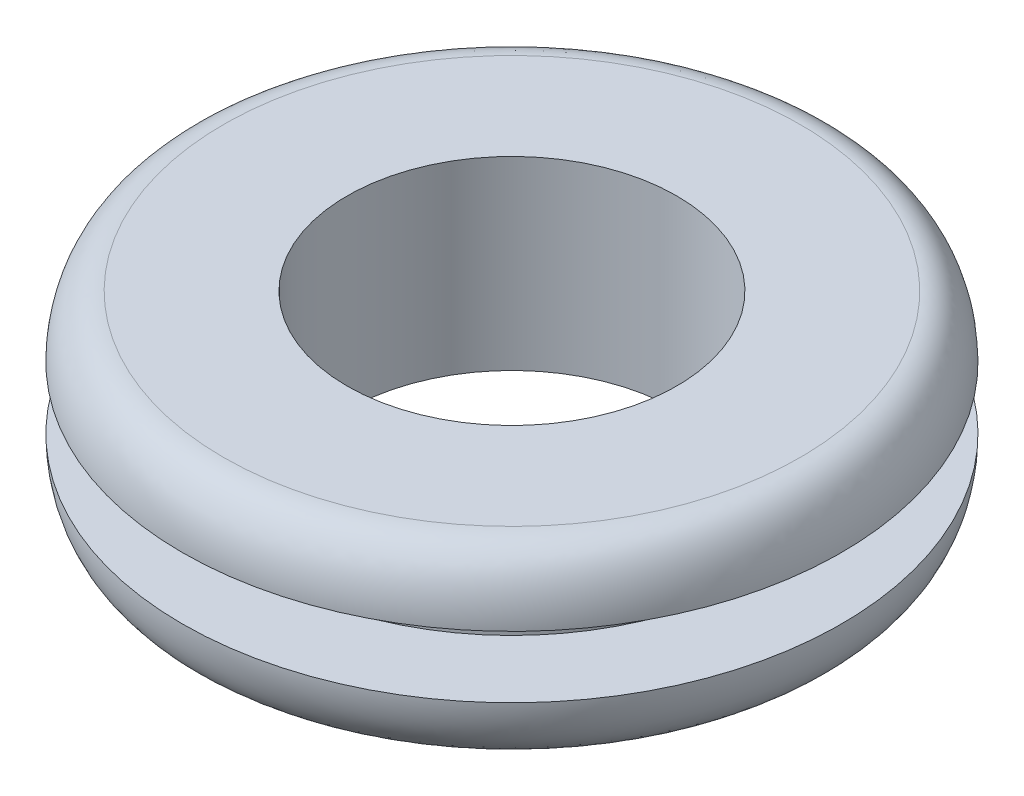
SolidWorks part; units mm, degrees
ref_plane "Front" through (0, 0, 0) normal (0, 0, 1) x (1, 0, 0)
ref_plane "Top" through (0, 0, 0) normal (0, 1, 0) x (1, 0, 0)
ref_plane "Right" through (0, 0, 0) normal (1, 0, 0) x (0, 0, -1)
sketch "Sketch1" plane through (0, 0, 0) normal (0, 0, 1) x (1, 0, 0)
  line L0 (-6.35, 3.5719) -> (-6.35, -3.5719)
  line L1 (-12.7, 1.1906) -> (-9.525, 1.1906)
  line L2 (-9.525, 1.1906) -> (-9.525, -1.1906)
  line L3 (-6.35, -3.5719) -> (-11.1125, -3.5719)
  line L4 (-6.35, 3.5719) -> (-11.1125, 3.5719)
  line L5 (-11.1125, 3.5719) -> (-11.1125, 1.1906) construction
  line L6 (-27.8997, 0) -> (0, 0) construction
  line L7 (55, 0) -> (-55, 0) construction
  line L8 (-12.7, -1.1906) -> (-9.525, -1.1906)
  line L9 (-12.7, -0.056) -> (-12.7, 2.4378) construction
  line L10 (-12.0259, 3.5719) -> (-10.1926, 3.5719) construction
  line L11 (0, 96.2646) -> (0, -76.2636) construction
  line L12 (0, -55) -> (0, 55) construction
  spline S0 degree 3 poles (-11.1125, 3.5719) (-12.2583, 3.5719) (-12.7, 2.2297) (-12.7, 1.1906) knots 0 0 0 0 1 1 1 1
  spline S1 degree 3 poles (-11.1125, -3.5719) (-12.2583, -3.5719) (-12.7, -2.2297) (-12.7, -1.1906) knots 0 0 0 0 1 1 1 1
  point P17 (-9.525, 0)
  dimension "D1" = 2.3813
  dimension "D2" = 9.525
  dimension "D3" = 6.35
  dimension "D4" = 7.1437
  dimension "D5" = 12.7
revolve "Revolve1" add sketch "Sketch1" angle 360 about L11
